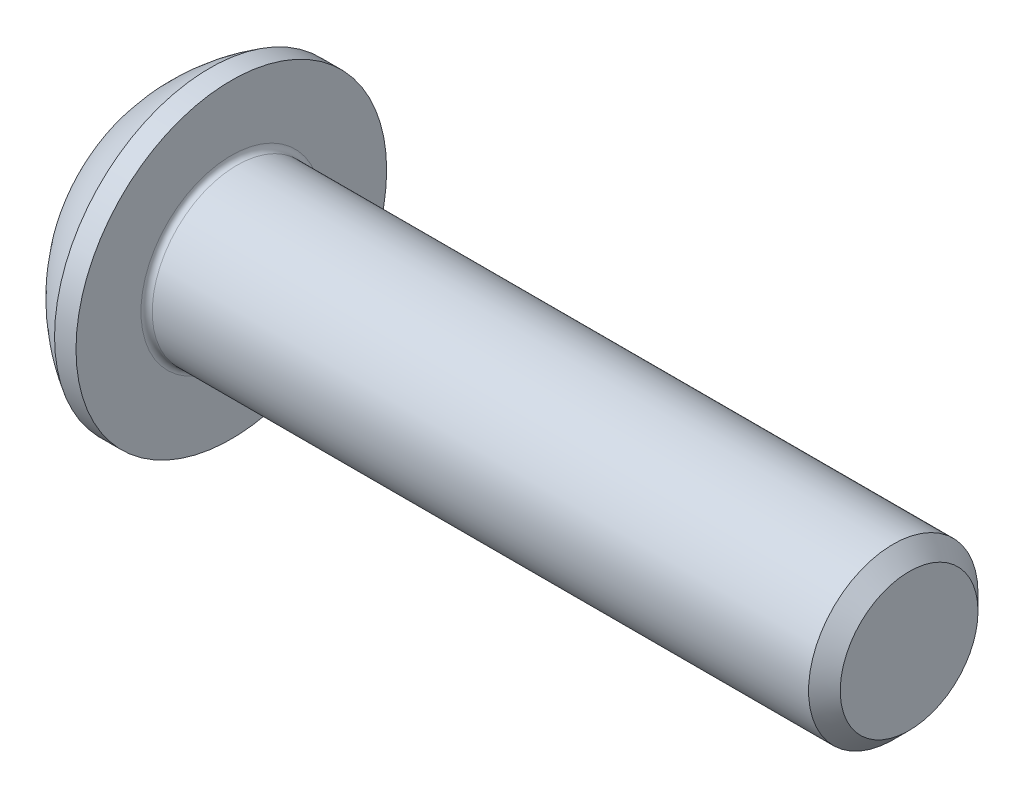
SolidWorks part; units mm, degrees
material "Plain Carbon Steel"
ref_plane "Front Plane" through (0, 0, 0) normal (0, 0, 1) x (1, 0, 0)
ref_plane "Top Plane" through (0, 0, 0) normal (0, 1, 0) x (1, 0, 0)
ref_plane "Right Plane" through (0, 0, 0) normal (1, 0, 0) x (0, 0, -1)
ref_plane "Plane1" through (0, 0, 0) normal (0, 0, -1) x (-1, 0, 0)
sketch "Sketch1" plane through (0, 0, 0) normal (0, 0, -1) x (-1, 0, 0)
  line L0 (-1.65, 2.75) -> (-1.65, 0)
  line L1 (-1.65, 0) -> (0, 0)
  line L2 (0, 0) -> (0, 1.425)
  line L3 (-1.27, 2.75) -> (-1.65, 2.75)
  line L4 (-1.65, 0) -> (0, 0) construction
  arc A0 (0, 1.425) -> (-1.27, 2.75) centre (-2.962, -0.1429) ccw
  dimension "D5" = 3.3514
  dimension "D1" = 2.75
  dimension "D2" = 1.65
  dimension "D3" = 1.425
  dimension "D4" = 0.38
revolve "Revolve1" add sketch "Sketch1" angle 360 about L4
sketch "Sketch2" plane through (0, 0, 0) normal (-1, 0, 0) x (0, 0, 1)
  line L7 (-1, 0.5774) -> (-1, -0.5774)
  line L8 (-1, -0.5774) -> (0, -1.1547)
  line L9 (0, -1.1547) -> (1, -0.5774)
  line L10 (1, -0.5774) -> (1, 0.5774)
  line L11 (1, 0.5774) -> (0, 1.1547)
  line L12 (0, 1.1547) -> (-1, 0.5774)
  circle A0 centre (0, 0) radius 1 construction
  dimension "D1" = 2
extrude "Cut-Extrude1" cut sketch "Sketch2" against normal blind 1.04
sketch "Sketch3" plane through (0, 0, 0) normal (0, 0, 1) x (1, 0, 0)
  line L0 (1.04, 1) -> (1.04, 0)
  line L1 (1.04, 0) -> (1.6174, 0)
  line L2 (1.6174, 0) -> (1.04, 1)
  line L3 (1.04, 0) -> (1.6174, 0) construction
revolve "Cut-Revolve1" cut sketch "Sketch3" angle 360 about L3
sketch "Sketch4" plane through (1.65, 0, 0) normal (1, 0, 0) x (0, 0, -1)
  circle A0 centre (0, 0) radius 1.5
extrude "Largo y Ancho rosca" add sketch "Sketch4" along normal blind 12
fillet "Fillet1" radius 0.1 1 edges at (1.65, 0, -1.5)
chamfer "Chamfer1" distance 0.2805 angle 45 1 edges at (13.65, 0, -1.5)
